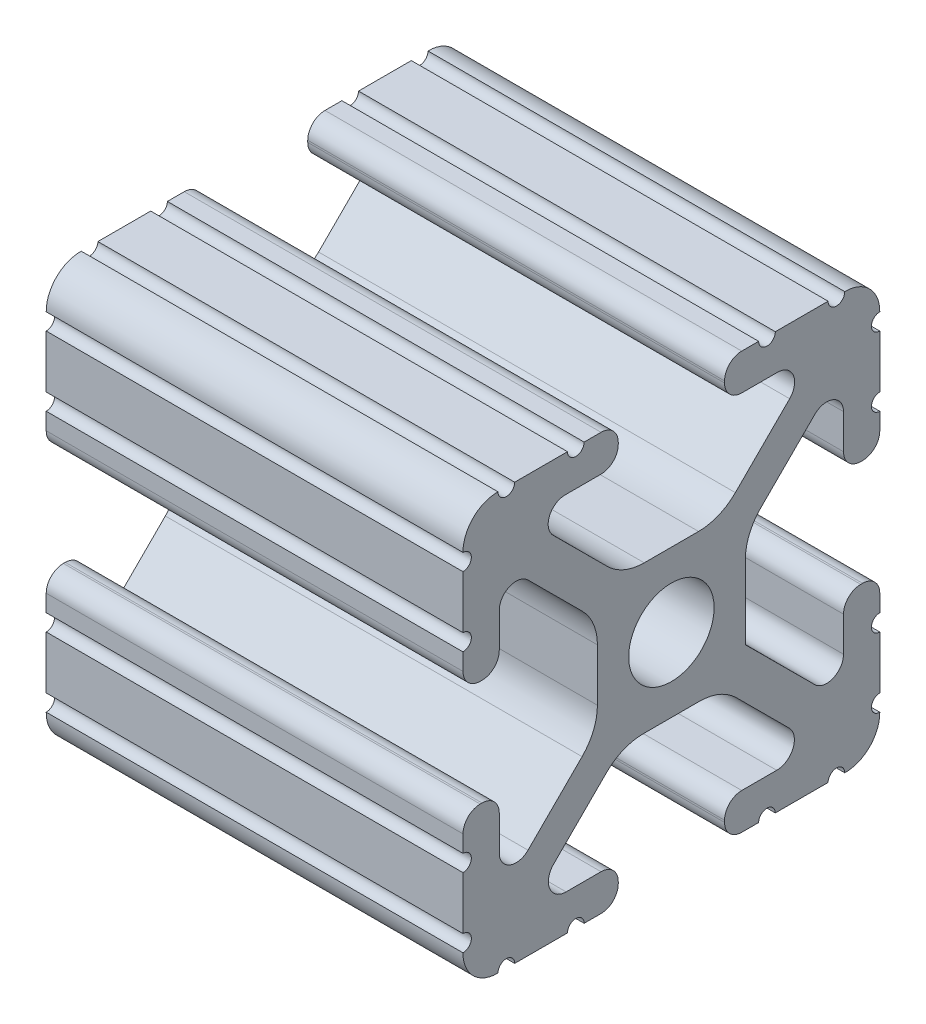
SolidWorks part; units mm, degrees
material "6061-T6 (SS)"
ref_plane "Front Plane" through (0, 0, 0) normal (0, 0, 1) x (1, 0, 0)
ref_plane "Top Plane" through (0, 0, 0) normal (0, 1, 0) x (1, 0, 0)
ref_plane "Right Plane" through (0, 0, 0) normal (1, 0, 0) x (0, 0, -1)
sketch "Sketch1" plane through (0, 0, 0) normal (1, 0, 0) x (0, 0, -1)
  line L0 (6.3331, -12.7) -> (9.5504, -12.7)
  line L1 (12.7, -9.5504) -> (12.7, -6.3331)
  line L2 (12.7, -5.3171) -> (12.7, -4.2875)
  line L3 (11.651, -3.2385) -> (11.5392, -3.2385)
  line L4 (10.4902, -4.2875) -> (10.4902, -6.4021)
  line L5 (8.7371, -7.1294) -> (4.5085, -2.9104)
  line L6 (4.5085, -2.9104) -> (4.5085, 1.5932)
  line L7 (5.441, 3.8408) -> (8.7371, 7.1294)
  line L8 (10.4902, 6.4021) -> (10.4902, 4.2875)
  line L9 (11.5392, 3.2385) -> (11.651, 3.2385)
  line L10 (12.7, 4.2875) -> (12.7, 5.3171)
  line L11 (12.7, 6.3331) -> (12.7, 9.5504)
  line L12 (9.5504, 12.7) -> (6.3331, 12.7)
  line L13 (5.3171, 12.7) -> (4.2875, 12.7)
  line L14 (3.2385, 11.651) -> (3.2385, 11.5392)
  line L15 (4.2875, 10.4902) -> (6.4768, 10.4902)
  line L16 (7.207, 8.7244) -> (3.8983, 5.4232)
  line L17 (1.6558, 4.4958) -> (-1.6558, 4.4958)
  line L18 (-3.8983, 5.4232) -> (-7.207, 8.7244)
  line L19 (-6.4768, 10.4902) -> (-4.2875, 10.4902)
  line L20 (-3.2385, 11.5392) -> (-3.2385, 11.651)
  line L21 (-4.2875, 12.7) -> (-5.3171, 12.7)
  line L22 (-6.3331, 12.7) -> (-9.5504, 12.7)
  line L23 (-12.7, 9.5504) -> (-12.7, 6.3331)
  line L24 (-12.7, 5.3171) -> (-12.7, 4.2875)
  line L25 (-11.651, 3.2385) -> (-11.5392, 3.2385)
  line L26 (-10.4902, 4.2875) -> (-10.4902, 6.4021)
  line L27 (-8.7371, 7.1294) -> (-5.441, 3.8408)
  line L28 (-4.5085, 1.5932) -> (-4.5085, -1.5932)
  line L29 (-5.441, -3.8408) -> (-8.7371, -7.1294)
  line L30 (-10.4902, -6.4021) -> (-10.4902, -4.2875)
  line L31 (-11.5392, -3.2385) -> (-11.651, -3.2385)
  line L32 (-12.7, -4.2875) -> (-12.7, -5.3171)
  line L33 (-12.7, -6.3331) -> (-12.7, -9.5504)
  line L34 (-9.5504, -12.7) -> (-6.3331, -12.7)
  line L35 (-5.3171, -12.7) -> (-4.2875, -12.7)
  line L36 (-3.2385, -11.651) -> (-3.2385, -11.5392)
  line L37 (-4.2875, -10.4902) -> (-6.4164, -10.4902)
  line L38 (-7.1797, -8.6452) -> (-3.9523, -5.4237)
  line L39 (-1.7093, -4.4958) -> (1.7093, -4.4958)
  line L40 (3.9523, -5.4237) -> (7.1797, -8.6452)
  line L41 (6.4164, -10.4902) -> (4.2875, -10.4902)
  line L42 (3.2385, -11.5392) -> (3.2385, -11.651)
  line L43 (4.2875, -12.7) -> (5.3171, -12.7)
  circle A0 centre (0, 0) radius 2.6035
  arc A1 (6.3331, -12.7) -> (5.3171, -12.7) centre (5.8251, -12.7) ccw
  arc A2 (10.5664, -12.6998) -> (9.5504, -12.7) centre (10.0584, -12.7) ccw
  arc A3 (10.5664, -12.6998) -> (12.6998, -10.5664) centre (10.5918, -10.5918) ccw
  arc A4 (12.7, -9.5504) -> (12.6998, -10.5664) centre (12.7, -10.0584) ccw
  arc A5 (12.7, -5.3171) -> (12.7, -6.3331) centre (12.7, -5.8251) ccw
  arc A6 (12.7, -4.2875) -> (11.651, -3.2385) centre (11.651, -4.2875) ccw
  arc A7 (11.5392, -3.2385) -> (10.4902, -4.2875) centre (11.5392, -4.2875) ccw
  arc A8 (8.7371, -7.1294) -> (10.4902, -6.4021) centre (9.4628, -6.4021) ccw
  arc A9 (5.441, 3.8408) -> (4.5085, 1.5932) centre (7.6835, 1.5932) ccw
  arc A10 (10.4902, 6.4021) -> (8.7371, 7.1294) centre (9.4628, 6.4021) ccw
  arc A11 (10.4902, 4.2875) -> (11.5392, 3.2385) centre (11.5392, 4.2875) ccw
  arc A12 (11.651, 3.2385) -> (12.7, 4.2875) centre (11.651, 4.2875) ccw
  arc A13 (12.7, 6.3331) -> (12.7, 5.3171) centre (12.7, 5.8251) ccw
  arc A14 (12.6998, 10.5664) -> (12.7, 9.5504) centre (12.7, 10.0584) ccw
  arc A15 (12.6998, 10.5664) -> (10.5664, 12.6998) centre (10.5918, 10.5918) ccw
  arc A16 (9.5504, 12.7) -> (10.5664, 12.6998) centre (10.0584, 12.7) ccw
  arc A17 (5.3171, 12.7) -> (6.3331, 12.7) centre (5.8251, 12.7) ccw
  arc A18 (4.2875, 12.7) -> (3.2385, 11.651) centre (4.2875, 11.651) ccw
  arc A19 (3.2385, 11.5392) -> (4.2875, 10.4902) centre (4.2875, 11.5392) ccw
  arc A20 (7.207, 8.7244) -> (6.4768, 10.4902) centre (6.4768, 9.4563) ccw
  arc A21 (1.6558, 4.4958) -> (3.8983, 5.4232) centre (1.6558, 7.6708) ccw
  arc A22 (-3.8983, 5.4232) -> (-1.6558, 4.4958) centre (-1.6558, 7.6708) ccw
  arc A23 (-6.4768, 10.4902) -> (-7.207, 8.7244) centre (-6.4768, 9.4563) ccw
  arc A24 (-4.2875, 10.4902) -> (-3.2385, 11.5392) centre (-4.2875, 11.5392) ccw
  arc A25 (-3.2385, 11.651) -> (-4.2875, 12.7) centre (-4.2875, 11.651) ccw
  arc A26 (-6.3331, 12.7) -> (-5.3171, 12.7) centre (-5.8251, 12.7) ccw
  arc A27 (-10.5664, 12.6998) -> (-9.5504, 12.7) centre (-10.0584, 12.7) ccw
  arc A28 (-10.5664, 12.6998) -> (-12.6998, 10.5664) centre (-10.5918, 10.5918) ccw
  arc A29 (-12.7, 9.5504) -> (-12.6998, 10.5664) centre (-12.7, 10.0584) ccw
  arc A30 (-12.7, 5.3171) -> (-12.7, 6.3331) centre (-12.7, 5.8251) ccw
  arc A31 (-12.7, 4.2875) -> (-11.651, 3.2385) centre (-11.651, 4.2875) ccw
  arc A32 (-11.5392, 3.2385) -> (-10.4902, 4.2875) centre (-11.5392, 4.2875) ccw
  arc A33 (-8.7371, 7.1294) -> (-10.4902, 6.4021) centre (-9.4628, 6.4021) ccw
  arc A34 (-4.5085, 1.5932) -> (-5.441, 3.8408) centre (-7.6835, 1.5932) ccw
  arc A35 (-5.441, -3.8408) -> (-4.5085, -1.5932) centre (-7.6835, -1.5932) ccw
  arc A36 (-10.4902, -6.4021) -> (-8.7371, -7.1294) centre (-9.4628, -6.4021) ccw
  arc A37 (-10.4902, -4.2875) -> (-11.5392, -3.2385) centre (-11.5392, -4.2875) ccw
  arc A38 (-11.651, -3.2385) -> (-12.7, -4.2875) centre (-11.651, -4.2875) ccw
  arc A39 (-12.7, -6.3331) -> (-12.7, -5.3171) centre (-12.7, -5.8251) ccw
  arc A40 (-12.6998, -10.5664) -> (-12.7, -9.5504) centre (-12.7, -10.0584) ccw
  arc A41 (-12.6998, -10.5664) -> (-10.5664, -12.6998) centre (-10.5918, -10.5918) ccw
  arc A42 (-9.5504, -12.7) -> (-10.5664, -12.6998) centre (-10.0584, -12.7) ccw
  arc A43 (-5.3171, -12.7) -> (-6.3331, -12.7) centre (-5.8251, -12.7) ccw
  arc A44 (-4.2875, -12.7) -> (-3.2385, -11.651) centre (-4.2875, -11.651) ccw
  arc A45 (-3.2385, -11.5392) -> (-4.2875, -10.4902) centre (-4.2875, -11.5392) ccw
  arc A46 (-7.1797, -8.6452) -> (-6.4164, -10.4902) centre (-6.4164, -9.4098) ccw
  arc A47 (-1.7093, -4.4958) -> (-3.9523, -5.4237) centre (-1.7093, -7.6708) ccw
  arc A48 (3.9523, -5.4237) -> (1.7093, -4.4958) centre (1.7093, -7.6708) ccw
  arc A49 (6.4164, -10.4902) -> (7.1797, -8.6452) centre (6.4164, -9.4098) ccw
  arc A50 (4.2875, -10.4902) -> (3.2385, -11.5392) centre (4.2875, -11.5392) ccw
  arc A51 (3.2385, -11.651) -> (4.2875, -12.7) centre (4.2875, -11.651) ccw
extrude "Boss-Extrude1" add sketch "Sketch1" along normal blind 25.4
